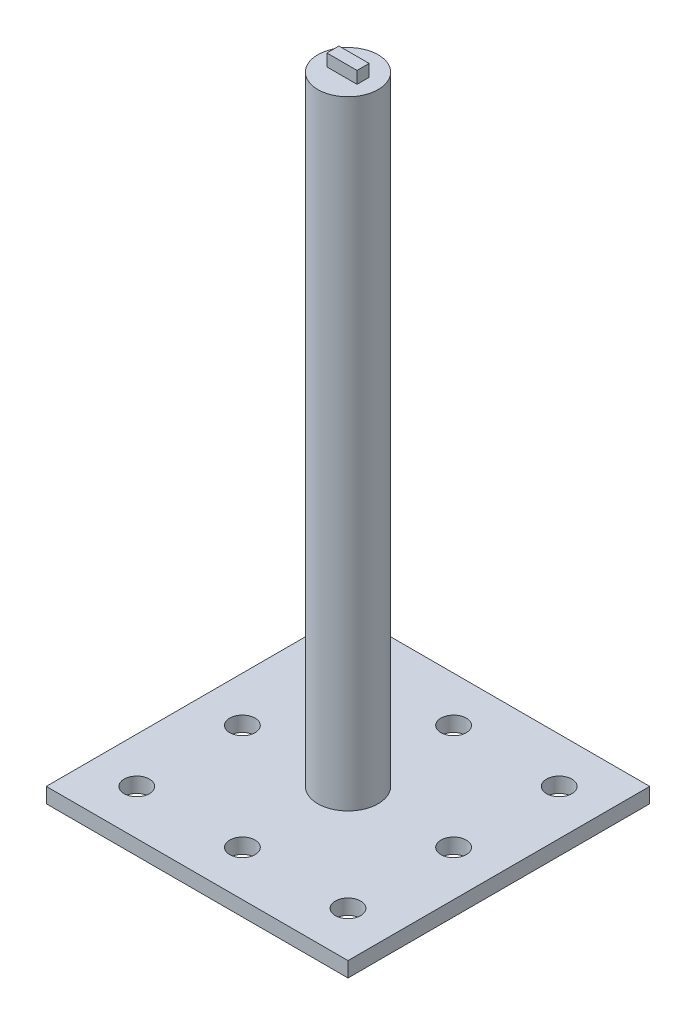
SolidWorks part; units mm, degrees
material "5052-H38"
ref_plane "Front Plane" through (0, 0, 0) normal (0, 0, 1) x (1, 0, 0)
ref_plane "Top Plane" through (0, 0, 0) normal (0, 1, 0) x (1, 0, 0)
ref_plane "Right Plane" through (0, 0, 0) normal (1, 0, 0) x (0, 0, -1)
sketch "Sketch1" plane through (0, 0, 0) normal (0, 1, 0) x (1, 0, 0)
  circle A0 centre (0, 0) radius 5
  circle A1 centre (0, 0) radius 4.5
  dimension "D1" = 10
  dimension "D2" = 0.5
extrude "Boss-Extrude1" add sketch "Sketch1" along normal blind 100
sketch "Sketch2" plane through (0, 100, 0) normal (0, 1, 0) x (1, 0, 0)
  circle A1 centre (0, 0) radius 5
  circle A2 centre (0, 0) radius 5
  dimension "D1" = 0
extrude "Boss-Extrude2" add sketch "Sketch2" along normal blind 2.5
sketch "Sketch3" plane through (0, 0, 0) normal (0, -1, 0) x (1, 0, 0)
  line L1 (25, 25) -> (-25, 25)
  line L2 (25, 25) -> (25, -25)
  line L3 (25, -25) -> (-25, -25)
  line L4 (-25, 25) -> (-25, -25)
  line L5 (0, -25) -> (0, 25) construction
  line L6 (25, 0) -> (-25, 0) construction
  point P0 (0, 0)
  dimension "D1" = 50
  dimension "D2" = 50
extrude "Boss-Extrude3" add sketch "Sketch3" along normal blind 2.5
hole_wizard "M5x0.8 Tapped Hole1" positions "Sketch5" profile "Sketch4" tap size "M5x0.8" standard "ANSI Metric"
sketch "Sketch5" plane through (0, 0, 0) normal (0, 1, 0) x (1, 0, 0)
  line L1 (-17.5, -17.5) -> (17.5, -17.5) construction
  line L2 (-17.5, -17.5) -> (-17.5, 17.5) construction
  line L3 (-17.5, 17.5) -> (17.5, 17.5) construction
  line L4 (17.5, -17.5) -> (17.5, 17.5) construction
  line L5 (0, 17.5) -> (0, -17.5) construction
  line L6 (-17.5, 0) -> (17.5, 0) construction
  point P0 (-17.5, 0)
  point P2 (-17.5, -17.5)
  point P4 (0, -17.5)
  point P6 (17.5, -17.5)
  point P8 (17.5, 0)
  point P10 (17.5, 17.5)
  point P12 (0, 17.5)
  point P14 (-17.5, 17.5)
  dimension "D1" = 35
sketch "Sketch4" plane through (-17.5, 0, 0) normal (1, 0, 0) x (0, 0, 1)
  line L0 (0, 0) -> (0, 15.2618)
  line L1 (0, 15.2618) -> (2.1, 14)
  line L2 (2.1, 14) -> (2.1, 0)
  line L5 (2.1, 0) -> (0, 0)
  line L10 (0, 15.2618) -> (-2.1, 14) construction
  line L11 (0, -6.35) -> (0, 107.95) construction
  dimension "Tap Drill Dia." = 4.2
  dimension "Tap Drill Depth" = 14
  dimension "Drill Angle" = 118
cosmetic thread "Hole Thread1" parameters "D1"=2.5, "D2"=5
cosmetic thread "Hole Thread2" parameters "D1"=2.5, "D2"=5
cosmetic thread "Hole Thread3" parameters "D1"=2.5, "D2"=5
cosmetic thread "Hole Thread4" parameters "D1"=2.5, "D2"=5
cosmetic thread "Hole Thread5" parameters "D1"=2.5, "D2"=5
cosmetic thread "Hole Thread6" parameters "D1"=2.5, "D2"=5
cosmetic thread "Hole Thread7" parameters "D1"=2.5, "D2"=5
cosmetic thread "Hole Thread8" parameters "D1"=2.5, "D2"=5
sketch "Sketch6" plane through (0, 102.5, 0) normal (0, 1, 0) x (1, 0, 0)
  line L1 (-2.5, 1) -> (2.5, 1)
  line L2 (-2.5, 1) -> (-2.5, -1)
  line L3 (-2.5, -1) -> (2.5, -1)
  line L4 (2.5, 1) -> (2.5, -1)
  line L5 (0, -1) -> (0, 1) construction
  line L6 (-2.5, 0) -> (2.5, 0) construction
  point P0 (0, 0)
  dimension "D1" = 2
  dimension "D2" = 5
extrude "Boss-Extrude5" add sketch "Sketch6" along normal blind 2
